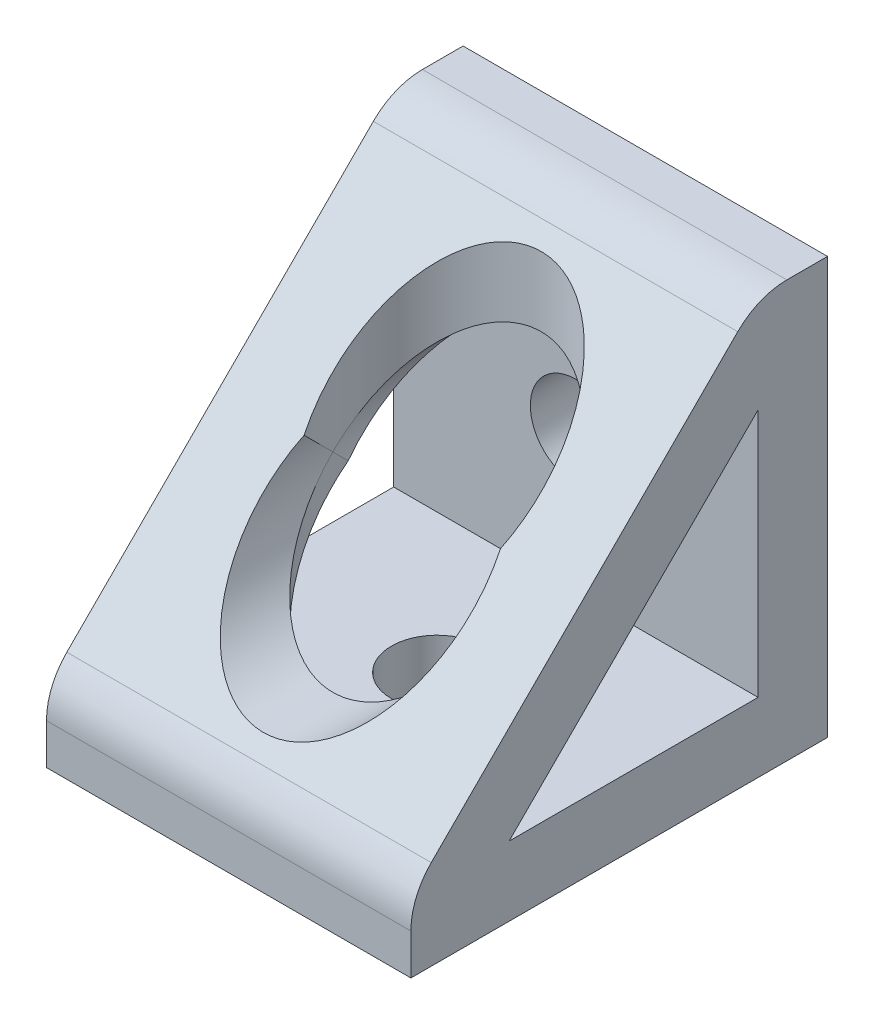
SolidWorks part; units mm, degrees
ref_plane "Front Plane" through (0, 0, 0) normal (0, 0, 1) x (1, 0, 0)
ref_plane "Top Plane" through (0, 0, 0) normal (0, 1, 0) x (1, 0, 0)
ref_plane "Right Plane" through (0, 0, 0) normal (1, 0, 0) x (0, 0, -1)
sketch "Sketch1" plane through (0, 0, 0) normal (1, 0, 0) x (0, 0, -1)
  line L0 (-19.05, -19.05) -> (19.05, -19.05) construction
  line L1 (19.05, -19.05) -> (19.05, 19.05) construction
  line L2 (19.05, 0) -> (0, 0) construction
  line L3 (0, -19.05) -> (0, 0) construction
  line L4 (-19.05, -19.05) -> (-19.05, -12.7) construction
  line L5 (19.05, 19.05) -> (12.7, 19.05) construction
  line L6 (-19.05, -12.7) -> (12.7, -12.7) construction
  line L7 (12.7, -12.7) -> (12.7, 19.05) construction
  line L8 (12.7, 0) -> (19.05, 0) construction
  line L9 (-4.1656, -12.7) -> (4.1656, -12.7)
  line L10 (-4.1656, -12.7) -> (-4.1656, -19.05)
  line L11 (-4.1656, -19.05) -> (4.1656, -19.05)
  line L12 (4.1656, -12.7) -> (4.1656, -19.05)
  line L17 (12.7, 4.1656) -> (19.05, 4.1656)
  line L18 (12.7, 4.1656) -> (12.7, -4.1656)
  line L19 (12.7, -4.1656) -> (19.05, -4.1656)
  line L20 (19.05, 4.1656) -> (19.05, -4.1656)
  line L26 (0, -12.7) -> (0, -19.05) construction
  line L28 (0, 0) -> (19.05, -19.05) construction
  line L31 (-19.05, -12.7) -> (12.7, 19.05) construction
  line L32 (-10.0697, -12.7) -> (12.7, 10.0697) construction
  point P43 (0, -19.05)
  dimension "Thickness" = 6.35
  dimension "Length (A)" = 38.1
  dimension "Length (B)" = 38.1
  dimension "For Screw Size" = 8.3312
  dimension "Mounting Hole Center to End" = 19.05
  dimension "D2" = 19.05
  dimension "D1" = 6.35
sketch "Sketch2" plane through (0, 0, 0) normal (0, 0, 1) x (1, 0, 0)
  line L0 (-16.6624, -19.05) -> (16.6624, -19.05) construction
  line L2 (-4.1656, -12.7) -> (4.1656, -12.7)
  line L6 (-4.1656, -12.7) -> (-4.1656, -19.05)
  line L7 (4.1656, -12.7) -> (4.1656, -19.05)
  line L8 (-16.6624, -12.7) -> (16.6624, -12.7) construction
  line L9 (0, 4.1656) -> (0, -4.1656) construction
  circle A1 centre (0, 0) radius 9.525
  point P3 (0, -19.05)
  point P8 (0, -12.7)
  point P13 (0, -12.7)
  point P16 (0, -19.05)
  dimension "Counterbore Diameter" = 19.05
  dimension "Bracket Width" = 33.3248
  dimension "D1" = 8.3312
sketch "Sketch3" plane through (0, 0, 0) normal (0, 1, 0) x (1, 0, 0)
  line L1 (-4.1656, 19.05) -> (4.1656, 19.05)
  line L2 (-4.1656, 19.05) -> (-4.1656, 12.7)
  line L3 (-4.1656, 12.7) -> (4.1656, 12.7)
  line L4 (4.1656, 19.05) -> (4.1656, 12.7)
  line L5 (0, 12.7) -> (0, 19.05) construction
  line L6 (-4.1656, 15.875) -> (4.1656, 15.875) construction
  line L9 (-16.6624, 12.7) -> (16.6624, 12.7) construction
  circle A1 centre (0, 0) radius 9.525
  point P0 (0, 15.875)
  point P17 (0, 19.05)
  dimension "D2" = 19.05
  dimension "D1" = 8.3312
  dimension "D3" = 33.3248
sketch "Sketch4" plane through (0, 0, 0) normal (1, 0, 0) x (0, 0, -1)
  line L0 (-19.05, -19.05) -> (19.05, -19.05)
  line L1 (19.05, -19.05) -> (19.05, 19.05)
  line L2 (-10.0697, -12.7) -> (12.7, -12.7)
  line L3 (12.7, -12.7) -> (12.7, 10.0697)
  line L4 (-19.05, -19.05) -> (-19.05, -15.3303)
  line L5 (-17.1901, -10.8401) -> (10.8401, 17.1901)
  line L6 (15.3303, 19.05) -> (19.05, 19.05)
  line L7 (-10.0697, -12.7) -> (12.7, 10.0697)
  arc A6 (15.3303, 19.05) -> (10.8401, 17.1901) centre (15.3303, 12.7) ccw
  arc A7 (-19.05, -15.3303) -> (-17.1901, -10.8401) centre (-12.7, -15.3303) cw
  point P9 (12.7, 19.05)
  point P16 (-19.05, -12.7)
  dimension "D1" = 6.35
extrude "Boss-Extrude1" add sketch "Sketch4" along normal mid plane 33.3248
sketch "Sketch5" plane through (0, -12.7, 0) normal (0, 1, 0) x (1, 0, 0)
  line L0 (0, -4.1656) -> (0, 4.1656) construction
  circle A0 centre (0, 0) radius 4.1656
  dimension "D1" = 8.3312
extrude "Cut-Extrude1" cut sketch "Sketch5" against normal up to next
sketch "Sketch6" plane through (0, 0, -12.7) normal (0, 0, 1) x (1, 0, 0)
  line L0 (0, 4.1656) -> (0, -4.1656) construction
  circle A0 centre (0, 0) radius 4.1656
  dimension "D1" = 8.3312
extrude "Cut-Extrude2" cut sketch "Sketch6" against normal up to next
sketch "Sketch27" plane through (0, 0, 19.05) normal (0, 0, 1) x (1, 0, 0)
  circle A0 centre (0, 0) radius 9.525 construction
  circle A2 centre (0, 0) radius 9.525
extrude "Cut-Extrude9" cut sketch "Sketch27" against normal up to surface (31.75 mm away) up to face at (4.1656, 0, -12.7)
sketch "Sketch28" plane through (0, 19.05, 0) normal (0, 1, 0) x (1, 0, 0)
  circle A0 centre (0, 0) radius 9.525 construction
  circle A2 centre (0, 0) radius 9.525
extrude "Cut-Extrude10" cut sketch "Sketch28" against normal up to surface (31.75 mm away) up to face at (0, -12.7, 4.1656)
equation "\"D2@Sketch1\"=\"Mounting Hole Center to End@Sketch1\""
equation "\"D1@Boss-Extrude1\"=\"Bracket Width@Sketch2\""
equation "\"D1@Sketch5\" = \"For Screw Size@Sketch1\""
equation "\"D1@Sketch2\"=\"For Screw Size@Sketch1\""
equation "\"D1@Sketch3\" = \"For Screw Size@Sketch1\""
equation "\"D1@Sketch1\"=\"Thickness@Sketch1\""
equation "\"D2@Sketch3\"=\"Counterbore Diameter@Sketch2\""
equation "\"D3@Sketch3\"=\"Bracket Width@Sketch2\""
equation "\"D1@Sketch6\"=\"For Screw Size@Sketch1\""
